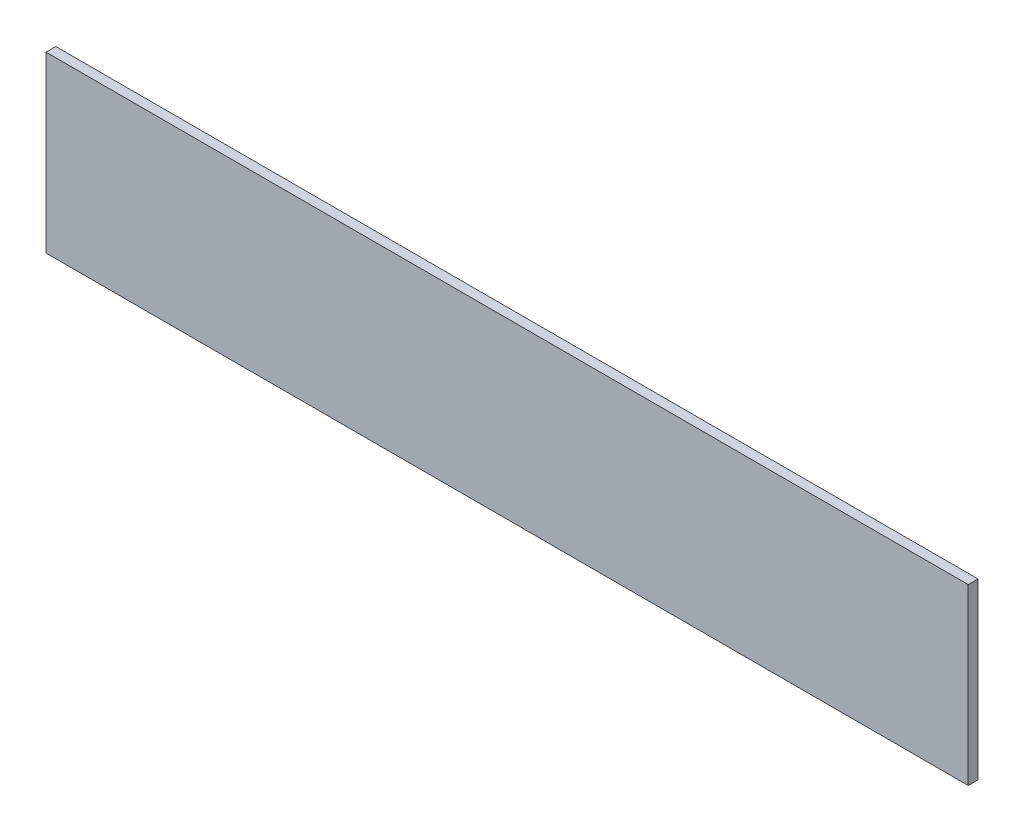
SolidWorks part; units mm, degrees
material "ABS"
ref_plane "X-Y Datum" through (0, 0, 0) normal (0, 0, 1) x (1, 0, 0)
ref_plane "X-Z Datum" through (0, 0, 0) normal (0, 1, 0) x (1, 0, 0)
ref_plane "Y-Z Datum" through (0, 0, 0) normal (1, 0, 0) x (0, 0, -1)
sketch "Sketch1" plane through (0, 0, 0) normal (0, 0, 1) x (1, 0, 0)
  line L1 (-149.85, 28.275) -> (149.85, 28.275)
  line L2 (-149.85, 28.275) -> (-149.85, -28.275)
  line L3 (-149.85, -28.275) -> (149.85, -28.275)
  line L4 (149.85, 28.275) -> (149.85, -28.275)
  line L5 (-149.85, 28.275) -> (149.85, -28.275) construction
  line L6 (-149.85, -28.275) -> (149.85, 28.275) construction
  point P0 (0, 0)
  dimension "D1" = 56.55
  dimension "D2" = 299.7
extrude "Boss-Extrude1" add sketch "Sketch1" along normal blind 3.175
